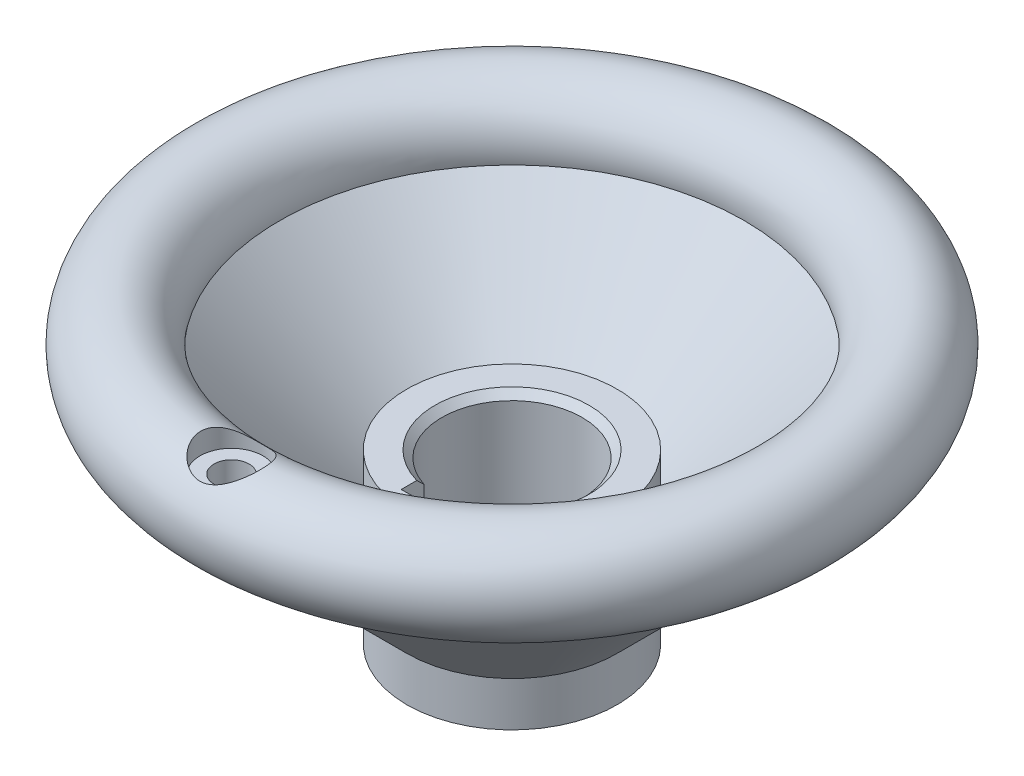
SolidWorks part; units mm, degrees
ref_plane "前视基准面" through (0, 0, 0) normal (0, 0, 1) x (1, 0, 0)
ref_plane "上视基准面" through (0, 0, 0) normal (0, 1, 0) x (1, 0, 0)
ref_plane "右视基准面" through (0, 0, 0) normal (1, 0, 0) x (0, 0, -1)
sketch "草图1" plane through (0, 0, 0) normal (0, 1, 0) x (1, 0, 0)
  circle A0 centre (0, 0) radius 7.5
  dimension "D1" = 15
extrude "凸台-拉伸1" add sketch "草图1" along normal blind 12
sketch "草图2" plane through (0, 0, 0) normal (0, 0, 1) x (1, 0, 0)
  line L0 (2.9822, 4.3107) -> (5.8107, 1.4822)
  line L1 (2.9822, 4.3107) -> (16.5548, 17.8832)
  line L2 (5.8107, 1.4822) -> (19.3832, 15.0548)
  line L3 (15.7664, 16.8452) -> (17.0558, 15.5558) construction
  line L4 (4.3964, 2.8964) -> (17.0558, 15.5558) construction
  line L5 (17.0558, 15.5558) -> (18.5919, 14.0197) construction
  line L6 (0, 0) -> (0, 22.5483) construction
  line L8 (8.25, 0) -> (-8.25, 0) construction
  arc A0 (19.3832, 15.0548) -> (16.5548, 17.8832) centre (20, 18.5) ccw
  arc A1 (16.5548, 17.8832) -> (19.3832, 15.0548) centre (20, 18.5) ccw construction
  point P14 (7.5, 6)
  dimension "D2" = 7
  dimension "D1" = 4
  dimension "D3" = 20
  dimension "D4" = 23.5
  dimension "D5" = 45
  dimension "D6" = 7.5
  dimension "D7" = 6
revolve "旋转1" add sketch "草图2" angle 360 about L6
sketch "草图3" plane through (0, 12, 0) normal (0, 1, 0) x (1, 0, 0)
  line L0 (1.5, -3.6) -> (1.5, -4.7697) construction
  line L1 (-1.5, -3.6) -> (1.5, -3.6) construction
  line L2 (-1.5, -4.7697) -> (-1.5, -6.4)
  line L3 (-1.5, -6.4) -> (1.5, -6.4)
  line L4 (1.5, -4.7697) -> (1.5, -6.4)
  line L5 (0, -5) -> (1.5, -6.4) construction
  line L6 (-1.5, -6.4) -> (0, -5) construction
  line L7 (0, -5) -> (1.5, -3.6) construction
  line L8 (-1.5, -3.6) -> (0, -5) construction
  line L9 (-1.5, -3.6) -> (-1.5, -4.7697) construction
  arc A0 (1.5, -4.7697) -> (-1.5, -4.7697) centre (0, 0) ccw
  arc A1 (-1.5, -4.7697) -> (0, -5) centre (0, 0) ccw construction
  arc A2 (0, -5) -> (1.5, -4.7697) centre (0, 0) ccw construction
  point P3 (0, -5)
  dimension "D1" = 10
  dimension "D2" = 11.4
  dimension "D3" = 3
extrude "切除-拉伸1" cut sketch "草图3" against normal through all
chamfer "倒角1" distance 0.5 angle 45 2 edges at (0, 0, -5) (0, 12, -5)
hole_wizard "孔1" positions "3D草图1" profile "草图4" legacy
sketch3d "3D草图1"
  line L0 (0, 22, 20) -> (0, 11.6423, 20)
  point P0 (0, 22, 20)
sketch "草图4" plane through (0, 22, 20) normal (1, 0, 0) x (0, 0, 1)
  line L0 (0, 0) -> (0, 1.5)
  line L1 (0, 1.5) -> (2.25, 1.5)
  line L2 (2.25, 1.5) -> (2.25, 0)
  line L3 (2.25, 0) -> (0, 0)
  line L4 (0, 110) -> (0, -10) construction
  dimension "直径" = 4.5
  dimension "深度" = 1.5
hole_wizard "M3 螺纹孔1" positions "草图5" profile "草图7" tap size "M3" standard "GB"
sketch "草图5" plane through (0, 20.5, 0) normal (0, 1, 0) x (1, 0, 0)
  point P0 (0, 0)
  point P4 (0, -20)
sketch "草图7" plane through (0, 20.5, 20) normal (1, 0, 0) x (0, 0, 1)
  line L0 (0, 0) -> (0, 4)
  line L1 (0, 4) -> (1.25, 3.2489)
  line L2 (1.25, 3.2489) -> (1.25, 0)
  line L5 (1.25, 0) -> (0, 0)
  line L10 (0, 4) -> (-1.25, 3.2489) construction
  line L11 (0, -6.35) -> (0, 107.95) construction
  dimension "螺纹孔钻头直径" = 2.5
  dimension "螺纹孔钻头深度" = 4
  dimension "导头角度" = 118
cosmetic thread "孔螺纹线1" parameters "D1"=4, "D2"=3
